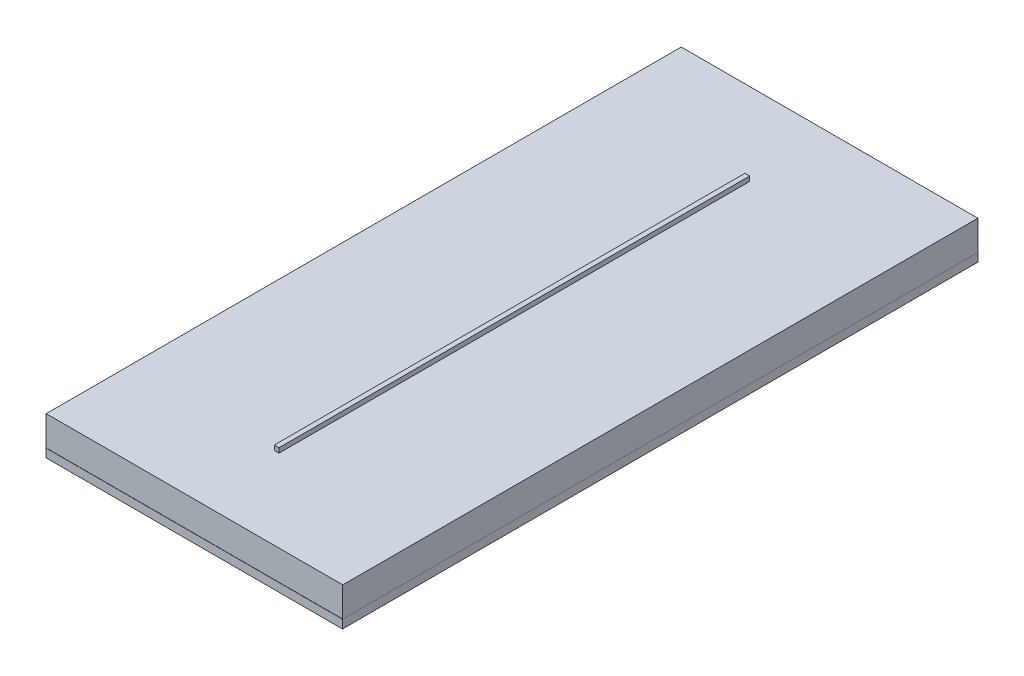
SolidWorks part; units mm, degrees
ref_plane "Front Plane" through (0, 0, 0) normal (0, 0, 1) x (1, 0, 0)
ref_plane "Top Plane" through (0, 0, 0) normal (0, 1, 0) x (1, 0, 0)
ref_plane "Right Plane" through (0, 0, 0) normal (1, 0, 0) x (0, 0, -1)
sketch "Sketch1" plane through (0, 0, 0) normal (0, 1, 0) x (1, 0, 0)
  line L1 (-34.995, 75) -> (34.995, 75)
  line L2 (-34.995, 75) -> (-34.995, -75)
  line L3 (-34.995, -75) -> (34.995, -75)
  line L4 (34.995, 75) -> (34.995, -75)
  line L5 (-34.995, 75) -> (34.995, -75) construction
  line L6 (-34.995, -75) -> (34.995, 75) construction
  point P0 (0, 0)
  dimension "D1" = 150
  dimension "D2" = 69.99
extrude "Boss-Extrude1" add sketch "Sketch1" along normal blind 2
sketch "Sketch2" plane through (0, 2, 0) normal (0, 1, 0) x (1, 0, 0)
  line L1 (-35, 74.95) -> (35, 74.95)
  line L2 (-35, 74.95) -> (-35, -74.95)
  line L3 (-35, -74.95) -> (35, -74.95)
  line L4 (35, 74.95) -> (35, -74.95)
  line L5 (-35, 74.95) -> (35, -74.95) construction
  line L6 (-35, -74.95) -> (35, 74.95) construction
  point P0 (0, 0)
  dimension "D1" = 149.9
  dimension "D2" = 70
extrude "Boss-Extrude3" add sketch "Sketch2" along normal blind 7
scale "Scale1" scale about centroid uniform scaling yes scale factor 5
scale "Scale2" scale about centroid uniform scaling yes scale factor 0.9
scale "Scale3" scale about centroid uniform scaling yes scale factor 0.1
sketch "Sketch3" plane through (0, 6.5248, 0) normal (0, 1, 0) x (1, 0, 0)
  line L1 (0.25, -25) -> (-0.25, -25)
  line L2 (0.25, -25) -> (0.25, 25)
  line L3 (0.25, 25) -> (-0.25, 25)
  line L4 (-0.25, -25) -> (-0.25, 25)
  line L5 (0.25, -25) -> (-0.25, 25) construction
  line L6 (0.25, 25) -> (-0.25, -25) construction
  point P0 (0, 0)
  dimension "D1" = 0.5
  dimension "D2" = 50
extrude "Boss-Extrude4" add sketch "Sketch3" along normal blind 0.5
